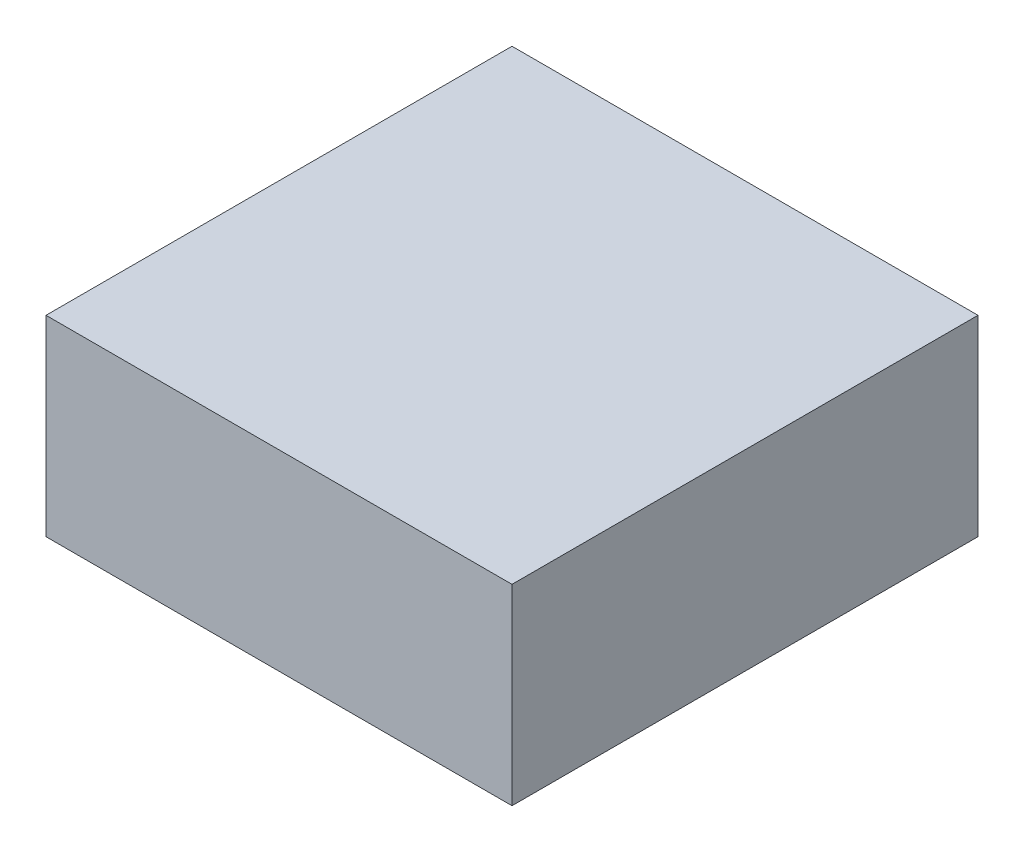
SolidWorks part; units mm, degrees
material "Кремний"
ref_plane "Спереди" through (0, 0, 0) normal (0, 0, 1) x (1, 0, 0)
ref_plane "Сверху" through (0, 0, 0) normal (0, 1, 0) x (1, 0, 0)
ref_plane "Справа" through (0, 0, 0) normal (1, 0, 0) x (0, 0, -1)
sketch "Эскиз1" plane through (0, 0, 0) normal (0, 1, 0) x (1, 0, 0)
  line L1 (0, 0) -> (1.13, 0)
  line L2 (0, 0) -> (0, -1.13)
  line L3 (0, -1.13) -> (1.13, -1.13)
  line L4 (1.13, 0) -> (1.13, -1.13)
  dimension "D1" = 1.13
  dimension "D2" = 1.13
extrude "Бобышка-Вытянуть1" add sketch "Эскиз1" along normal blind 0.465
